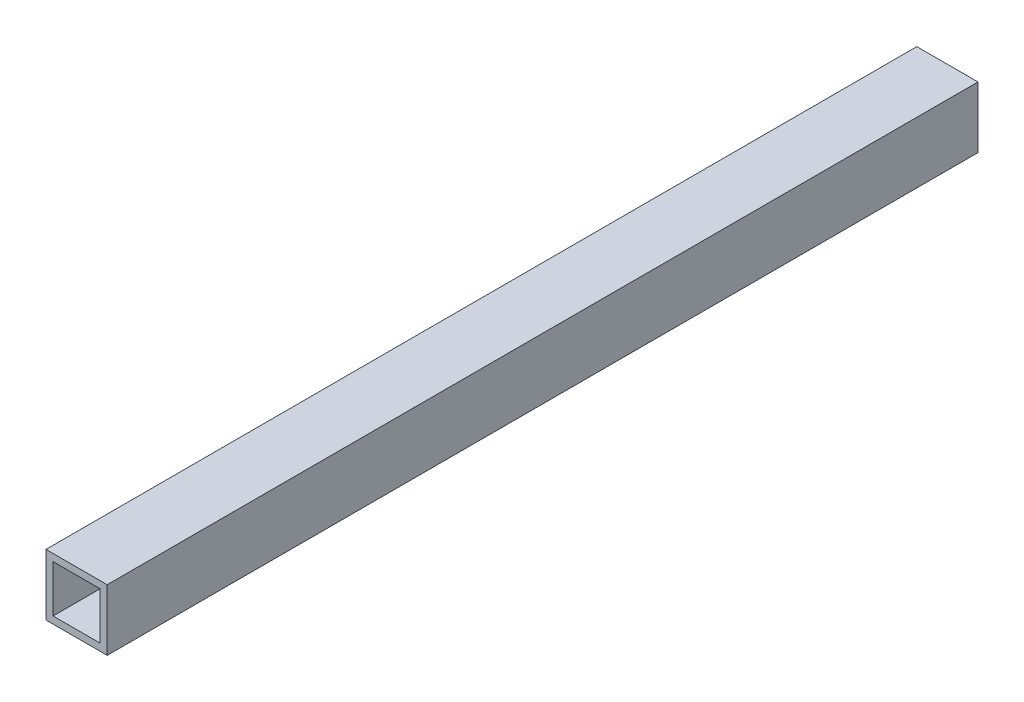
SolidWorks part; units mm, degrees
ref_plane "Front Plane" through (0, 0, 0) normal (0, 0, 1) x (1, 0, 0)
ref_plane "Top Plane" through (0, 0, 0) normal (0, 1, 0) x (1, 0, 0)
ref_plane "Right Plane" through (0, 0, 0) normal (1, 0, 0) x (0, 0, -1)
sketch "Sketch1" plane through (0, 0, 0) normal (0, 0, 1) x (1, 0, 0)
  line L1 (-6.5, 6.5) -> (6.5, 6.5)
  line L2 (-6.5, 6.5) -> (-6.5, -6.5)
  line L3 (-6.5, -6.5) -> (6.5, -6.5)
  line L4 (6.5, 6.5) -> (6.5, -6.5)
  line L5 (-6.5, 6.5) -> (6.5, -6.5) construction
  line L6 (-6.5, -6.5) -> (6.5, 6.5) construction
  line L7 (-5, -5) -> (5, -5)
  line L8 (-5, -5) -> (-5, 5)
  line L9 (-5, 5) -> (5, 5)
  line L10 (5, -5) -> (5, 5)
  line L11 (-5, -5) -> (5, 5) construction
  line L12 (-5, 5) -> (5, -5) construction
  point P0 (0, 0)
  point P6 (0, 0)
  dimension "D1" = 13
  dimension "D2" = 13
  dimension "D3" = 1.5
extrude "Boss-Extrude1" add sketch "Sketch1" along normal blind 185
